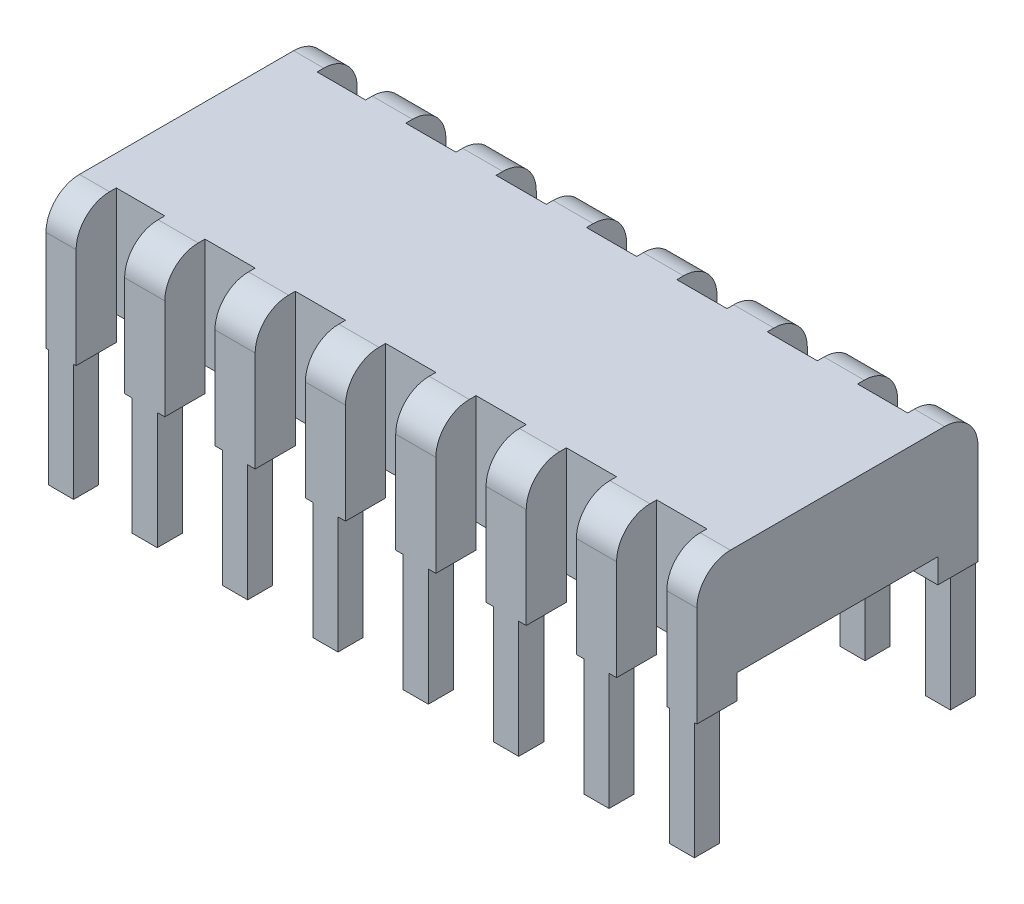
SolidWorks part; units mm, degrees
ref_plane "Front Plane" through (0, 0, 0) normal (0, 0, 1) x (1, 0, 0)
ref_plane "Top Plane" through (0, 0, 0) normal (0, 1, 0) x (1, 0, 0)
ref_plane "Right Plane" through (0, 0, 0) normal (1, 0, 0) x (0, 0, -1)
sketch "Sketch1" plane through (0, 0, 0) normal (0, 1, 0) x (1, 0, 0)
  line L1 (0, 0) -> (19.45, 0)
  line L2 (0, 0) -> (0, 6)
  line L3 (0, 6) -> (19.45, 6)
  line L4 (19.45, 0) -> (19.45, 6)
  dimension "D1" = 6
  dimension "D2" = 19.45
extrude "Boss-Extrude1" add sketch "Sketch1" along normal blind 3.27
sketch "Sketch2" plane through (0, 3.27, 0) normal (0, 1, 0) x (1, 0, 0)
  line L0 (0, 0) -> (19.45, 0) construction
  line L1 (19.45, 0) -> (18.55, 0)
  line L2 (19.45, 0) -> (19.45, -1.2)
  line L3 (19.45, -1.2) -> (18.55, -1.2)
  line L4 (18.55, 0) -> (18.55, -1.2)
  line L5 (17.05, 0) -> (15.85, 0)
  line L6 (17.05, 0) -> (17.05, -1.2)
  line L7 (17.05, -1.2) -> (15.85, -1.2)
  line L8 (15.85, 0) -> (15.85, -1.2)
  line L9 (19.45, 3) -> (0, 3)
  line L10 (14.35, 0) -> (13.15, 0)
  line L11 (14.35, 0) -> (14.35, -1.2)
  line L12 (14.35, -1.2) -> (13.15, -1.2)
  line L13 (13.15, 0) -> (13.15, -1.2)
  line L14 (11.65, 0) -> (10.45, 0)
  line L15 (11.65, 0) -> (11.65, -1.2)
  line L16 (11.65, -1.2) -> (10.45, -1.2)
  line L17 (10.45, 0) -> (10.45, -1.2)
  line L18 (8.95, 0) -> (7.75, 0)
  line L19 (8.95, 0) -> (8.95, -1.2)
  line L20 (8.95, -1.2) -> (7.75, -1.2)
  line L21 (7.75, 0) -> (7.75, -1.2)
  line L22 (6.25, 0) -> (5.05, 0)
  line L23 (6.25, 0) -> (6.25, -1.2)
  line L24 (6.25, -1.2) -> (5.05, -1.2)
  line L25 (5.05, 0) -> (5.05, -1.2)
  line L26 (3.55, 0) -> (2.35, 0)
  line L27 (3.55, 0) -> (3.55, -1.2)
  line L28 (3.55, -1.2) -> (2.35, -1.2)
  line L29 (2.35, 0) -> (2.35, -1.2)
  line L30 (0, 0) -> (0.9, 0)
  line L31 (0, 0) -> (0, -1.2)
  line L32 (0, -1.2) -> (0.9, -1.2)
  line L33 (0.9, 0) -> (0.9, -1.2)
  line L34 (19.45, 0) -> (19.45, 6) construction
  line L35 (0, 6) -> (0, 0) construction
  line L36 (0, 7.2) -> (0.9, 7.2)
  line L37 (0.9, 6) -> (0.9, 7.2)
  line L38 (0, 6) -> (0.9, 6)
  line L39 (0, 6) -> (0, 7.2)
  line L40 (3.55, 7.2) -> (2.35, 7.2)
  line L41 (2.35, 6) -> (2.35, 7.2)
  line L42 (3.55, 6) -> (2.35, 6)
  line L43 (3.55, 6) -> (3.55, 7.2)
  line L44 (6.25, 7.2) -> (5.05, 7.2)
  line L45 (5.05, 6) -> (5.05, 7.2)
  line L46 (6.25, 6) -> (5.05, 6)
  line L47 (6.25, 6) -> (6.25, 7.2)
  line L48 (8.95, 7.2) -> (7.75, 7.2)
  line L49 (7.75, 6) -> (7.75, 7.2)
  line L50 (8.95, 6) -> (7.75, 6)
  line L51 (8.95, 6) -> (8.95, 7.2)
  line L52 (11.65, 7.2) -> (10.45, 7.2)
  line L53 (10.45, 6) -> (10.45, 7.2)
  line L54 (11.65, 6) -> (10.45, 6)
  line L55 (11.65, 6) -> (11.65, 7.2)
  line L56 (14.35, 7.2) -> (13.15, 7.2)
  line L57 (13.15, 6) -> (13.15, 7.2)
  line L58 (14.35, 6) -> (13.15, 6)
  line L59 (14.35, 6) -> (14.35, 7.2)
  line L60 (17.05, 7.2) -> (15.85, 7.2)
  line L61 (15.85, 6) -> (15.85, 7.2)
  line L62 (17.05, 6) -> (15.85, 6)
  line L63 (17.05, 6) -> (17.05, 7.2)
  line L64 (19.45, 7.2) -> (18.55, 7.2)
  line L65 (18.55, 6) -> (18.55, 7.2)
  line L66 (19.45, 6) -> (18.55, 6)
  line L67 (19.45, 6) -> (19.45, 7.2)
  line M35 (0, 0) -> (19.45, 0)
  line M37 (19.45, 6) -> (0, 6)
  dimension "D1" = 1.2
  dimension "D2" = 0.9
  dimension "D3" = 1.2
  dimension "D4" = 0.9
  dimension "D5" = 1.2
  dimension "D6" = 1.2
  dimension "D7" = 1.2
  dimension "D8" = 1.2
  dimension "D9" = 1.2
  dimension "D10" = 1.5
  dimension "D11" = 1.5
  dimension "D12" = 1.5
  dimension "D13" = 1.5
  dimension "D14" = 1.5
  dimension "D15" = 1.5
  dimension "D16" = 1.45
extrude "Boss-Extrude2" add sketch "Sketch2" against normal blind 4 contours L4 L3 L2 M35 | L8 L7 L6 M35 | L13 L12 L11 M35 | L17 L16 L15 M35 | L21 L20 L19 M35 | L25 L24 L23 M35 | L29 L28 L27 M35 | L33 L31 L32 M35 | L39 L37 L36 M37 | L43 L40 L41 M37 | L47 L44 L45 M37 | L51 L48 L49 M37 | L55 L52 L53 M37 | L59 L56 L57 M37 | L63 L60 L61 M37 | L67 L64 L65 M37
fillet "Fillet1" radius 1 16 edges at (0.45, 3.27, 1.2) (2.95, 3.27, 1.2) (5.65, 3.27, 1.2) (8.35, 3.27, 1.2) (11.05, 3.27, 1.2) (13.75, 3.27, 1.2) (16.45, 3.27, 1.2) (19, 3.27, 1.2) (0.45, 3.27, -7.2) (2.95, 3.27, -7.2) (5.65, 3.27, -7.2) (8.35, 3.27, -7.2) (11.05, 3.27, -7.2) (13.75, 3.27, -7.2) (16.45, 3.27, -7.2) (19, 3.27, -7.2)
sketch "Sketch3" plane through (0, -0.73, 0) normal (0, -1, 0) x (1, 0, 0)
  line L0 (19.45, -7.2) -> (18.55, -7.2) construction
  line L1 (19.375, -7.2) -> (18.625, -7.2)
  line L2 (19.375, -7.2) -> (19.375, -6.45)
  line L3 (19.375, -6.45) -> (18.625, -6.45)
  line L4 (18.625, -7.2) -> (18.625, -6.45)
  line L5 (18.55, -6) -> (18.55, -7.2) construction
  line L6 (19.45, -6) -> (19.45, -7.2) construction
  line L7 (17.05, -7.2) -> (15.85, -7.2) construction
  line L8 (16.825, -7.2) -> (16.075, -7.2)
  line L9 (16.825, -7.2) -> (16.825, -6.45)
  line L10 (16.825, -6.45) -> (16.075, -6.45)
  line L11 (16.075, -7.2) -> (16.075, -6.45)
  line L12 (15.85, -6) -> (15.85, -7.2) construction
  line L13 (17.05, -6) -> (17.05, -7.2) construction
  line L14 (14.35, -7.2) -> (13.15, -7.2) construction
  line L15 (14.125, -7.2) -> (13.375, -7.2)
  line L16 (14.125, -7.2) -> (14.125, -6.45)
  line L17 (14.125, -6.45) -> (13.375, -6.45)
  line L18 (13.375, -7.2) -> (13.375, -6.45)
  line L19 (11.65, -7.2) -> (10.45, -7.2) construction
  line L20 (11.425, -7.2) -> (10.675, -7.2)
  line L21 (11.425, -7.2) -> (11.425, -6.45)
  line L22 (11.425, -6.45) -> (10.675, -6.45)
  line L23 (10.675, -7.2) -> (10.675, -6.45)
  line L24 (14.35, -6) -> (14.35, -7.2) construction
  line L25 (13.15, -6) -> (13.15, -7.2) construction
  line L26 (10.45, -6) -> (10.45, -7.2) construction
  line L27 (11.65, -6) -> (11.65, -7.2) construction
  line L28 (9.7, -6) -> (9.7, 0)
  line L29 (10.45, -6) -> (8.95, -6) construction
  line L30 (8.95, 0) -> (10.45, 0) construction
  line L31 (7.975, -6.45) -> (8.725, -6.45)
  line L32 (8.725, -7.2) -> (8.725, -6.45)
  line L33 (7.975, -7.2) -> (8.725, -7.2)
  line L34 (7.975, -7.2) -> (7.975, -6.45)
  line L35 (5.275, -6.45) -> (6.025, -6.45)
  line L36 (6.025, -7.2) -> (6.025, -6.45)
  line L37 (5.275, -7.2) -> (6.025, -7.2)
  line L38 (5.275, -7.2) -> (5.275, -6.45)
  line L39 (2.575, -6.45) -> (3.325, -6.45)
  line L40 (3.325, -7.2) -> (3.325, -6.45)
  line L41 (2.575, -7.2) -> (3.325, -7.2)
  line L42 (2.575, -7.2) -> (2.575, -6.45)
  line L43 (19.45, -3) -> (0, -3)
  line L44 (19.45, 0) -> (19.45, -6) construction
  line L45 (0, -6) -> (0, 0) construction
  line L46 (2.575, 1.2) -> (2.575, 0.45)
  line L47 (2.575, 1.2) -> (3.325, 1.2)
  line L48 (3.325, 1.2) -> (3.325, 0.45)
  line L49 (2.575, 0.45) -> (3.325, 0.45)
  line L50 (5.275, 1.2) -> (5.275, 0.45)
  line L51 (5.275, 1.2) -> (6.025, 1.2)
  line L52 (6.025, 1.2) -> (6.025, 0.45)
  line L53 (5.275, 0.45) -> (6.025, 0.45)
  line L54 (7.975, 1.2) -> (7.975, 0.45)
  line L55 (7.975, 1.2) -> (8.725, 1.2)
  line L56 (8.725, 1.2) -> (8.725, 0.45)
  line L57 (7.975, 0.45) -> (8.725, 0.45)
  line L58 (11.425, 0.45) -> (10.675, 0.45)
  line L59 (10.675, 1.2) -> (10.675, 0.45)
  line L60 (11.425, 1.2) -> (10.675, 1.2)
  line L61 (11.425, 1.2) -> (11.425, 0.45)
  line L62 (14.125, 0.45) -> (13.375, 0.45)
  line L63 (13.375, 1.2) -> (13.375, 0.45)
  line L64 (14.125, 1.2) -> (13.375, 1.2)
  line L65 (14.125, 1.2) -> (14.125, 0.45)
  line L66 (16.825, 0.45) -> (16.075, 0.45)
  line L67 (16.075, 1.2) -> (16.075, 0.45)
  line L68 (16.825, 1.2) -> (16.075, 1.2)
  line L69 (16.825, 1.2) -> (16.825, 0.45)
  line L70 (19.45, 1.2) -> (18.55, 1.2) construction
  line L71 (19.375, 1.2) -> (18.625, 1.2)
  line L72 (19.375, 1.2) -> (19.375, 0.45)
  line L73 (19.375, 0.45) -> (18.625, 0.45)
  line L74 (18.625, 1.2) -> (18.625, 0.45)
  line L75 (18.55, 0) -> (18.55, 1.2) construction
  line L76 (0, 1.2) -> (0.9, 1.2) construction
  line L77 (0.825, 0.45) -> (0.075, 0.45)
  line L78 (0.825, 0.45) -> (0.825, 1.2)
  line L79 (0.825, 1.2) -> (0.075, 1.2)
  line L80 (0.075, 0.45) -> (0.075, 1.2)
  line L81 (0, 0) -> (0, 1.2) construction
  line L82 (0, -7.2) -> (0.9, -7.2) construction
  line L83 (0.825, -7.2) -> (0.075, -7.2)
  line L84 (0.825, -7.2) -> (0.825, -6.45)
  line L85 (0.825, -6.45) -> (0.075, -6.45)
  line L86 (0.075, -7.2) -> (0.075, -6.45)
  line L87 (0, -6) -> (0, -7.2) construction
  line M40 (0.9, 1.2) -> (0, 1.2)
  dimension "D1" = 0.75
  dimension "D2" = 0.75
  dimension "D3" = 0.075
  dimension "D4" = 0.075
  dimension "D5" = 0.75
  dimension "D6" = 0.75
  dimension "D7" = 0.225
  dimension "D8" = 0.225
  dimension "D9" = 0.75
  dimension "D10" = 0.75
  dimension "D11" = 0.225
  dimension "D12" = 0.225
  dimension "D13" = 0.75
  dimension "D14" = 0.75
  dimension "D15" = 0.225
  dimension "D16" = 0.225
  dimension "D17" = 0.75
  dimension "D18" = 0.075
  dimension "D19" = 0.75
  dimension "D20" = 0.075
  dimension "D21" = 0.75
  dimension "D22" = 0.75
  dimension "D23" = 0.075
extrude "Boss-Extrude3" add sketch "Sketch3" along normal blind 3.5 contours L71 L74 L73 L72 | L69 L68 L67 L66 | L65 L64 L63 L62 | L61 L60 L59 L58 | L54 L57 L56 L55 | L50 L53 L52 L51 | L46 L49 L48 L47 | L80 L77 L78 M40 | L86 L83 L84 L85 | L42 L41 L40 L39 | L38 L37 L36 L35 | L23 L20 L21 L22 | L34 L33 L32 L31 | L18 L15 L16 L17 | L11 L8 L9 L10 | L4 L1 L2 L3
